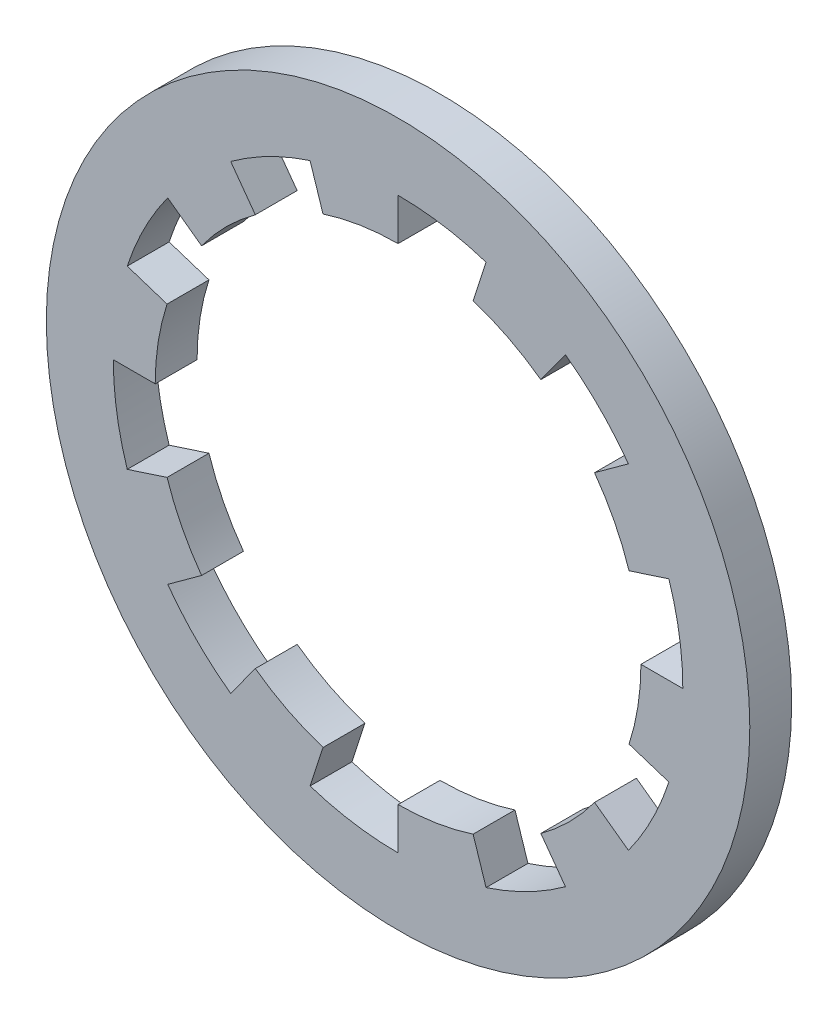
SolidWorks part; units mm, degrees
ref_plane "Płaszczyzna przednia" through (0, 0, 0) normal (0, 0, 1) x (1, 0, 0)
ref_plane "Płaszczyzna górna" through (0, 0, 0) normal (0, 1, 0) x (1, 0, 0)
ref_plane "Płaszczyzna prawa" through (0, 0, 0) normal (1, 0, 0) x (0, 0, -1)
sketch "Sketch1" plane through (0, 0, 0) normal (0, 0, 1) x (1, 0, 0)
  circle A0 centre (0, 0) radius 14.5
  circle A1 centre (0, 0) radius 21
  dimension "D1" = 29
  dimension "D2" = 42
extrude "Boss-Extrude1" add sketch "Sketch1" along normal blind 2.5
sketch "Sketch2" plane through (0, 0, 2.5) normal (0, 0, 1) x (1, 0, 0)
  line L0 (0, 0) -> (0, 17)
  line L1 (0, 0) -> (5.2533, 16.168)
  line L2 (0, 0) -> (9.9923, 13.7533)
  line L3 (0, 0) -> (13.7533, 9.9923)
  line L4 (0, 0) -> (16.168, 5.2533)
  line L5 (0, 0) -> (17, 0)
  line L6 (0, 0) -> (16.168, -5.2533)
  line L7 (0, 0) -> (13.7533, -9.9923)
  line L8 (0, 0) -> (9.9923, -13.7533)
  line L9 (0, 0) -> (5.2533, -16.168)
  line L10 (0, 0) -> (0, -17)
  line L11 (0, 0) -> (-5.2533, -16.168)
  line L12 (0, 0) -> (-9.9923, -13.7533)
  line L13 (0, 0) -> (-13.7533, -9.9923)
  line L14 (0, 0) -> (-16.168, -5.2533)
  line L15 (0, 0) -> (-17, 0)
  line L16 (0, 0) -> (-16.168, 5.2533)
  line L17 (0, 0) -> (-13.7533, 9.9923)
  line L18 (0, 0) -> (-9.9923, 13.7533)
  line L19 (0, 0) -> (-5.2533, 16.168)
  circle A0 centre (0, 0) radius 17
  point P24 (0, 0)
  circle M5 centre (0, 0) radius 14.5
  dimension "D2" = 20
  dimension "D1" = 17
extrude "Cut-Extrude1" cut sketch "Sketch2" against normal blind 4 contours L1 A0 L0 M5 | L3 A0 L2 M5 | L5 A0 L4 M5 | L7 A0 L6 M5 | L9 A0 L8 M5 | L11 A0 L10 M5 | L13 A0 L12 M5 | L15 A0 L14 M5 | L17 A0 L16 M5 | L19 A0 L18 M5
